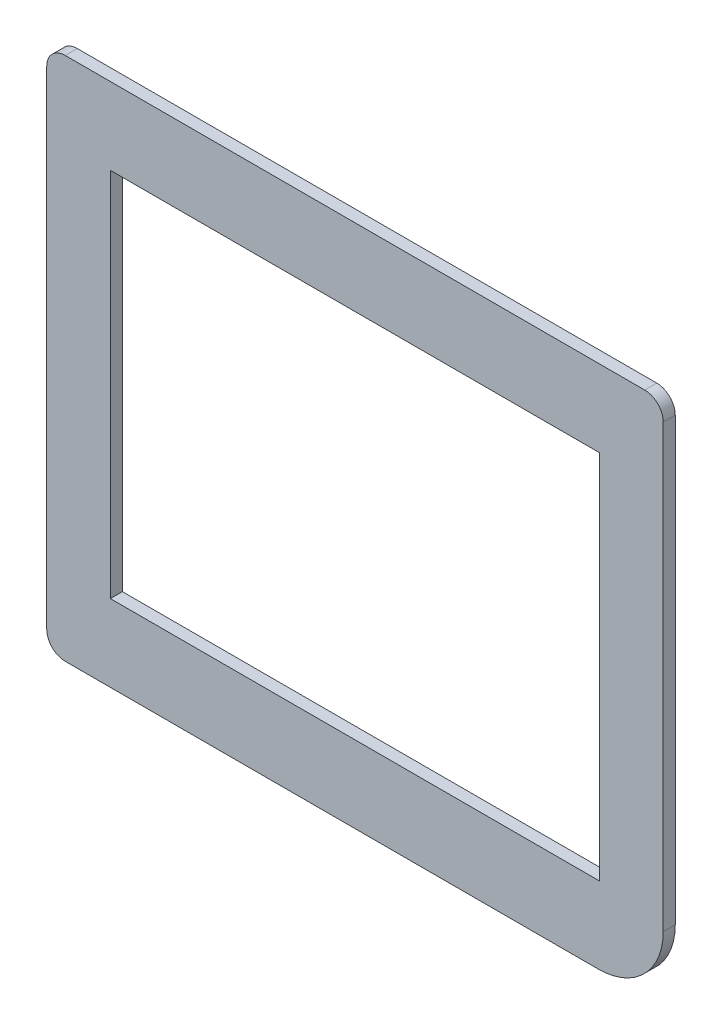
SolidWorks part; units mm, degrees
ref_plane "Front Plane" through (0, 0, 0) normal (0, 0, 1) x (1, 0, 0)
ref_plane "Top Plane" through (0, 0, 0) normal (0, 1, 0) x (1, 0, 0)
ref_plane "Right Plane" through (0, 0, 0) normal (1, 0, 0) x (0, 0, -1)
sketch "Sketch1" plane through (0, 0, 0) normal (0, 0, 1) x (1, 0, 0)
  line L0 (0, 28.35) -> (0, -28.35) construction
  line L1 (-31.31, 28.35) -> (31.31, 28.35)
  line L2 (-33.31, 26.35) -> (-33.31, -26.35)
  line L3 (-31.31, -28.35) -> (26.31, -28.35)
  line L4 (33.31, 26.35) -> (33.31, -21.35)
  arc A0 (26.31, -28.35) -> (33.31, -21.35) centre (26.31, -21.35) ccw
  arc A1 (31.31, 28.35) -> (33.31, 26.35) centre (31.31, 26.35) cw
  arc A2 (-31.31, 28.35) -> (-33.31, 26.35) centre (-31.31, 26.35) ccw
  arc A3 (-33.31, -26.35) -> (-31.31, -28.35) centre (-31.31, -26.35) ccw
  point P10 (33.31, 28.35)
  point P13 (-33.31, 28.35)
  dimension "D3" = 7
  dimension "D4" = 2
  dimension "D1" = 56.7
  dimension "D2" = 66.62
extrude "Boss-Extrude1" add sketch "Sketch1" along normal blind 1.3
sketch "Sketch2" plane through (0, 0, 0) normal (0, 0, -1) x (-1, 0, 0)
  line L0 (-26.44, -20.04) -> (-26.44, 20.04) construction
  line L1 (26.44, -20.04) -> (-26.44, -20.04)
  line L2 (26.44, -20.04) -> (26.44, 20.04)
  line L3 (26.44, 20.04) -> (-26.44, 20.04)
  line L4 (-26.44, -20.04) -> (-26.44, 20.04)
  line L5 (26.44, -20.04) -> (-26.44, 20.04) construction
  line L6 (26.44, 20.04) -> (-26.44, -20.04) construction
  point P0 (0, 0)
extrude "Cut-Extrude1" cut sketch "Sketch2" against normal through all
